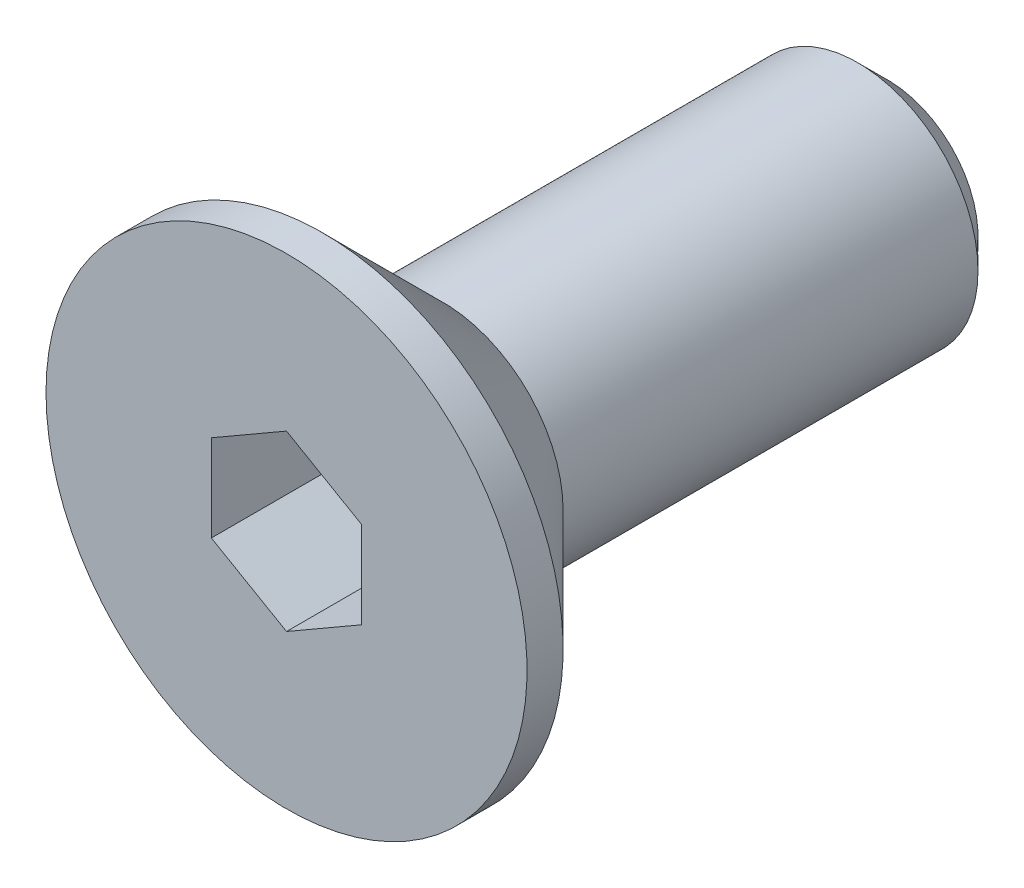
SolidWorks part; units mm, degrees
ref_plane "前视基准面" through (0, 0, 0) normal (0, 0, 1) x (1, 0, 0)
ref_plane "上视基准面" through (0, 0, 0) normal (0, 1, 0) x (1, 0, 0)
ref_plane "右视基准面" through (0, 0, 0) normal (1, 0, 0) x (0, 0, -1)
sketch "草图1" plane through (0, 0, 0) normal (1, 0, 0) x (0, 0, -1)
  line L0 (-5, 0) -> (-5, 4)
  line L1 (-5, 4) -> (-4.4, 4)
  line L2 (-4.4, 4) -> (-2.4, 2)
  line L3 (-2.4, 2) -> (5, 2)
  line L5 (5, 2) -> (5, 0)
  line L6 (5, 0) -> (-5, 0)
  dimension "D1" = 45
  dimension "D2" = 2
  dimension "D3" = 10
  dimension "D4" = 4
  dimension "D5" = 2.6
revolve "旋转1" add sketch "草图1" angle 360 about L6
chamfer "倒角1" distance 0.5 angle 45 1 edges at (-2, 0, -5)
sketch "草图2" plane through (0, 0, 5) normal (0, 0, 1) x (1, 0, 0)
  line L1 (0, 1.4434) -> (-1.25, 0.7217)
  line L2 (-1.25, 0.7217) -> (-1.25, -0.7217)
  line L3 (-1.25, -0.7217) -> (0, -1.4434)
  line L4 (0, -1.4434) -> (1.25, -0.7217)
  line L5 (1.25, -0.7217) -> (1.25, 0.7217)
  line L6 (1.25, 0.7217) -> (0, 1.4434)
  circle A0 centre (0, 0) radius 1.25 construction
  dimension "D1" = 2.5
extrude "切除-拉伸1" cut sketch "草图2" against normal blind 2.5
